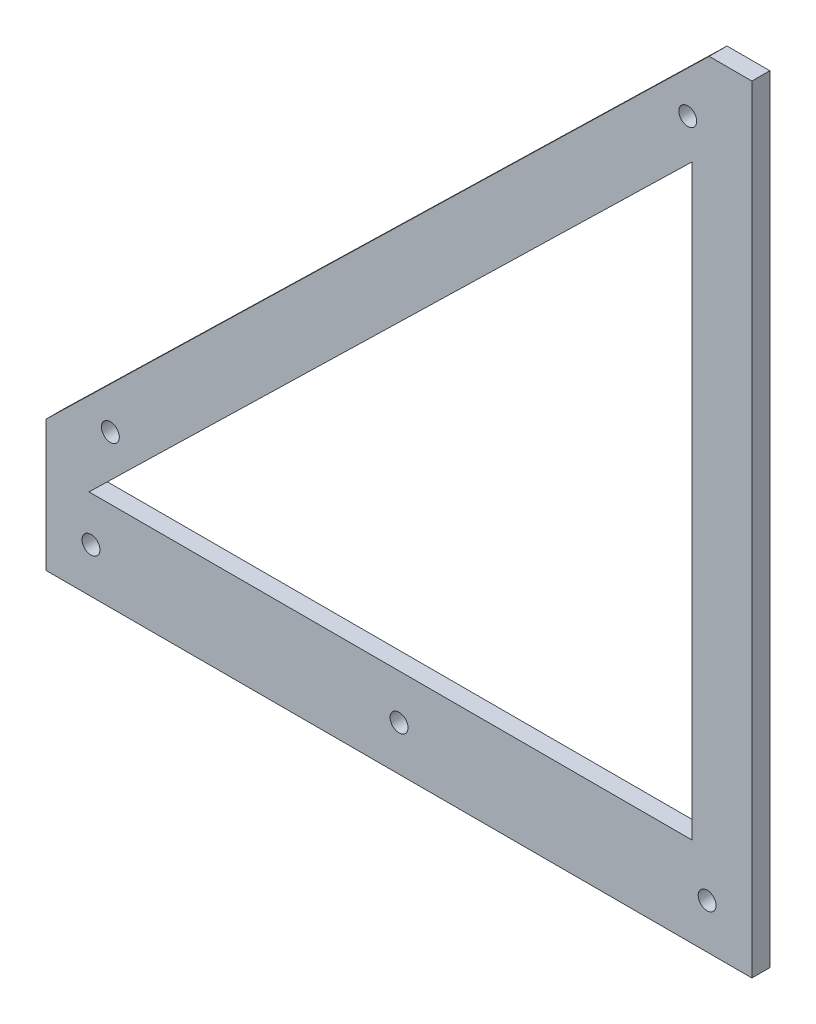
SolidWorks part; units mm, degrees
ref_plane "Front Plane" through (0, 0, 0) normal (0, 0, 1) x (1, 0, 0)
ref_plane "Top Plane" through (0, 0, 0) normal (0, 1, 0) x (1, 0, 0)
ref_plane "Right Plane" through (0, 0, 0) normal (1, 0, 0) x (0, 0, -1)
sketch "Sketch2" plane through (0, 0, 0) normal (0, 0, 1) x (1, 0, 0)
  line L0 (0, 0) -> (462.0877, 450) construction
  line L1 (0, 0) -> (118.2085, 0)
  line L2 (0, 0) -> (0, 115.1163)
  line L3 (0, 115.1163) -> (118.2085, 115.1163)
  line L5 (0, 6.9792) -> (111.0418, 115.1163)
  line L6 (7.1667, 0) -> (118.2085, 108.1371)
  line L7 (0, 0) -> (0, -15)
  line L8 (0, -15) -> (118.2085, -15)
  line L9 (118.2085, -15) -> (118.2085, 0)
  line L10 (118.2085, 115.1163) -> (118.2085, 0)
  line L11 (108.2085, 98.3987) -> (108.2085, 0)
  circle A0 centre (10.7462, 10.4651) radius 1.5
  circle A1 centre (107.4622, 104.6512) radius 1.5
  circle A2 centre (7.5, -7.5) radius 1.5
  circle A3 centre (59.1042, -7.5) radius 1.5
  circle A4 centre (110.7085, -7.5) radius 1.5
  point P24 (0, -7.5)
  point P25 (59.1042, -15)
  dimension "D7" = 3
  dimension "D14" = 3
  dimension "D1" = 645
  dimension "D2" = 165
  dimension "D3" = 450
  dimension "D4" = 45.759
  dimension "D5" = 135
  dimension "D6" = 15
  dimension "D8" = 5
  dimension "D9" = 5
  dimension "D10" = 15
  dimension "D11" = 10
  dimension "D12" = 7.5
  dimension "D13" = 7.5
  dimension "D15" = 7.5
extrude "Boss-Extrude1" add sketch "Sketch2" along normal blind 3
